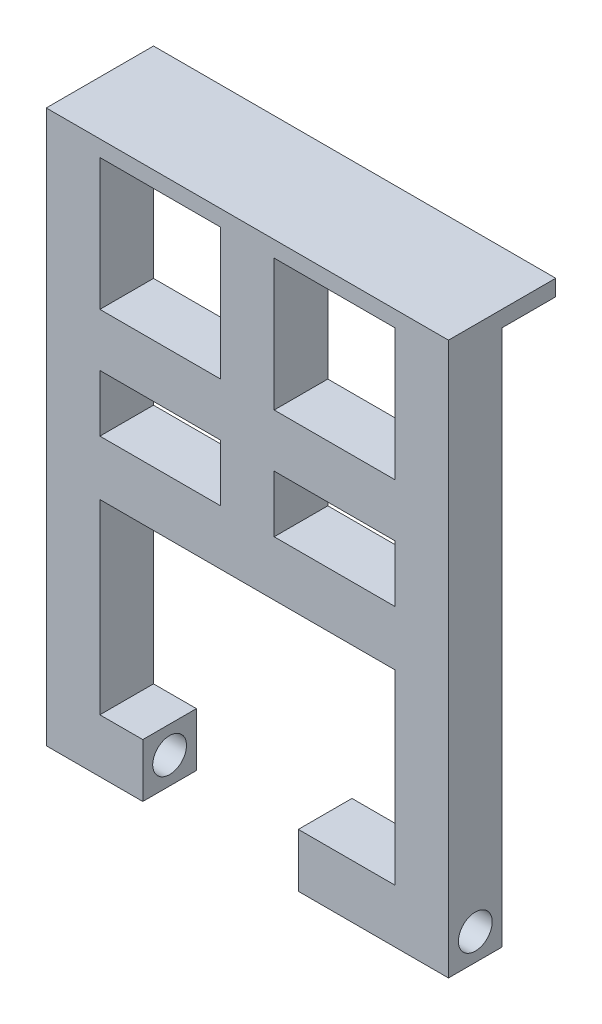
SolidWorks part; units mm, degrees
ref_plane "Front Plane" through (0, 0, 0) normal (0, 0, 1) x (1, 0, 0)
ref_plane "Top Plane" through (0, 0, 0) normal (0, 1, 0) x (1, 0, 0)
ref_plane "Right Plane" through (0, 0, 0) normal (1, 0, 0) x (0, 0, -1)
sketch "Sketch1" plane through (0, 0, 0) normal (0, 1, 0) x (1, 0, 0)
  line L1 (0, 0) -> (75, 0)
  line L2 (0, 0) -> (0, 20)
  line L3 (0, 20) -> (75, 20)
  line L4 (75, 0) -> (75, 20)
  dimension "D1" = 75
  dimension "D2" = 20
extrude "Boss-Extrude1" add sketch "Sketch1" along normal blind 3
sketch "Sketch2" plane through (0, 0, 0) normal (0, 0, 1) x (1, 0, 0)
  line L1 (0, 0) -> (10, 0)
  line L2 (0, 0) -> (0, -100)
  line L3 (0, -100) -> (10, -100)
  line L4 (10, 0) -> (10, -100)
  line L5 (75, 0) -> (65, 0)
  line L6 (75, 0) -> (75, -100)
  line L7 (75, -100) -> (65, -100)
  line L8 (65, 0) -> (65, -100)
  dimension "D1" = 100
  dimension "D2" = 10
  dimension "D3" = 10
extrude "Boss-Extrude2" add sketch "Sketch2" against normal blind 10
sketch "Sketch5" plane through (0, 0, 0) normal (0, 0, 1) x (1, 0, 0)
  line L0 (10, -100) -> (65, -100) construction
  line L1 (37.5, -100) -> (37.5, -84.2438) construction
  line L3 (10, -100) -> (18, -100)
  line L4 (10, -100) -> (10, -90)
  line L5 (10, -90) -> (18, -90)
  line L6 (18, -100) -> (18, -90)
  line L7 (65, -100) -> (47, -100)
  line L8 (65, -100) -> (65, -90)
  line L9 (65, -90) -> (47, -90)
  line L10 (47, -100) -> (47, -90)
  dimension "D1" = 19.5
  dimension "D2" = 9.5
  dimension "D3" = 10
  dimension "D4" = 10
extrude "Boss-Extrude3" add sketch "Sketch5" against normal blind 10
sketch "Sketch7" plane through (18, 0, 0) normal (1, 0, 0) x (0, 0, -1)
  line L0 (0, -100) -> (0, -90) construction
  line L1 (10, -100) -> (0, -100) construction
  circle A0 centre (5, -95) radius 3.15
  dimension "D1" = 6.3
  dimension "D2" = 5
  dimension "D3" = 5
extrude "Cut-Extrude1" cut sketch "Sketch7" against normal through all both and the other way through all
sketch "Sketch9" plane through (0, 0, 0) normal (0, 0, 1) x (1, 0, 0)
  line L0 (38.3659, 0) -> (65, -51.2225)
  line L3 (10, 0) -> (65, 0) construction
  line L4 (65, 0) -> (65, -90) construction
  line L5 (27.0948, 0) -> (38.3659, 0)
  line L6 (27.0948, 0) -> (37.2621, -19.5535)
  line L7 (65, -51.2225) -> (65, -72.8989)
  line L8 (37.2621, -19.5535) -> (10, -33.7289)
  line L11 (10, -90) -> (10, 0) construction
  line L12 (10, -45) -> (41.8754, -28.4258)
  line L13 (41.8754, -28.4258) -> (65, -72.8989)
  line L14 (10, -33.7289) -> (10, -45)
  dimension "D1" = 51.2225
extrude "Boss-Extrude4" [suppressed] add sketch "Sketch9" against normal blind 10 contours L0 L7 L13 L12 L14 L8 L6 L5
sketch "Sketch13" plane through (0, 0, 0) normal (0, 0, 1) x (1, 0, 0)
  line L0 (37.5, 0) -> (37.5, -61.48) construction
  line L1 (10, 0) -> (65, 0) construction
  line L2 (10, -24.5309) -> (32.5, -24.5309)
  line L3 (10, -90) -> (10, 0) construction
  line L4 (65, 0) -> (65, -90) construction
  line L5 (10, -34.3944) -> (32.5, -34.3944)
  line L6 (10, -45) -> (32.5, -45)
  line L7 (10, -55.2331) -> (32.5, -55.2331)
  line L8 (32.5, 0) -> (32.5, -24.5309)
  line L9 (42.5, 0) -> (42.5, -24.5309)
  line L10 (10, -24.5309) -> (10, -34.3944)
  line L11 (32.5, 0) -> (32.5, -61.48) construction
  line L12 (42.5, 0) -> (42.5, -61.48) construction
  line L13 (65, -24.5309) -> (65, -34.3944)
  line L14 (10, -45) -> (10, -55.2331)
  line L15 (65, -45) -> (65, -55.2331)
  line L16 (32.5, -34.3944) -> (32.5, -45)
  line L17 (42.5, -34.3944) -> (42.5, -45)
  line L18 (42.5, -24.5309) -> (65, -24.5309)
  line L19 (42.5, -34.3944) -> (65, -34.3944)
  line L20 (42.5, -45) -> (65, -45)
  line L21 (42.5, -55.2331) -> (65, -55.2331)
  line L22 (32.5, -55.2331) -> (42.5, -55.2331)
  line L23 (32.5, 0) -> (42.5, 0)
  dimension "D1" = 5
  dimension "D2" = 5
extrude "Boss-Extrude5" add sketch "Sketch13" against normal blind 10
sketch "Sketch14" plane through (0, 0, -10) normal (0, 0, -1) x (-1, 0, 0)
  line L21 (0, -100) -> (0, 0)
  line L22 (0, 0) -> (-10, 0)
  line L23 (-10, 0) -> (-10, -24.5309)
  line L24 (-10, -24.5309) -> (-32.5, -24.5309)
  line L25 (-32.5, -24.5309) -> (-32.5, 0)
  line L26 (-32.5, 0) -> (-42.5, 0)
  line L27 (-42.5, 0) -> (-42.5, -24.5309)
  line L28 (-42.5, -24.5309) -> (-65, -24.5309)
  line L29 (-65, -24.5309) -> (-65, 0)
  line L30 (-65, 0) -> (-75, 0)
  line L31 (-75, 0) -> (-75, -100)
  line L32 (-75, -100) -> (-47, -100)
  line L33 (-47, -100) -> (-47, -90)
  line L34 (-47, -90) -> (-65, -90)
  line L35 (-65, -90) -> (-65, -55.2331)
  line L36 (-65, -55.2331) -> (-10, -55.2331)
  line L37 (-10, -55.2331) -> (-10, -90)
  line L38 (-10, -90) -> (-18, -90)
  line L39 (-18, -90) -> (-18, -100)
  line L40 (-18, -100) -> (0, -100)
  line L41 (0, -100) -> (0, 0)
  line L42 (0, 0) -> (-10, 0)
  line L43 (-10, 0) -> (-10, -24.5309)
  line L44 (-10, -24.5309) -> (-32.5, -24.5309)
  line L45 (-32.5, -24.5309) -> (-32.5, 0)
  line L46 (-32.5, 0) -> (-42.5, 0)
  line L47 (-42.5, 0) -> (-42.5, -24.5309)
  line L48 (-42.5, -24.5309) -> (-65, -24.5309)
  line L49 (-65, -24.5309) -> (-65, 0)
  line L50 (-65, 0) -> (-75, 0)
  line L51 (-75, 0) -> (-75, -100)
  line L52 (-75, -100) -> (-47, -100)
  line L53 (-47, -100) -> (-47, -90)
  line L54 (-47, -90) -> (-65, -90)
  line L55 (-65, -90) -> (-65, -55.2331)
  line L56 (-65, -55.2331) -> (-10, -55.2331)
  line L57 (-10, -55.2331) -> (-10, -90)
  line L58 (-10, -90) -> (-18, -90)
  line L59 (-18, -90) -> (-18, -100)
  line L60 (-18, -100) -> (0, -100)
  dimension "D1" = 0
  dimension "D2" = 100
  dimension "D3" = 28
  dimension "D4" = 18
  dimension "D5" = 10
